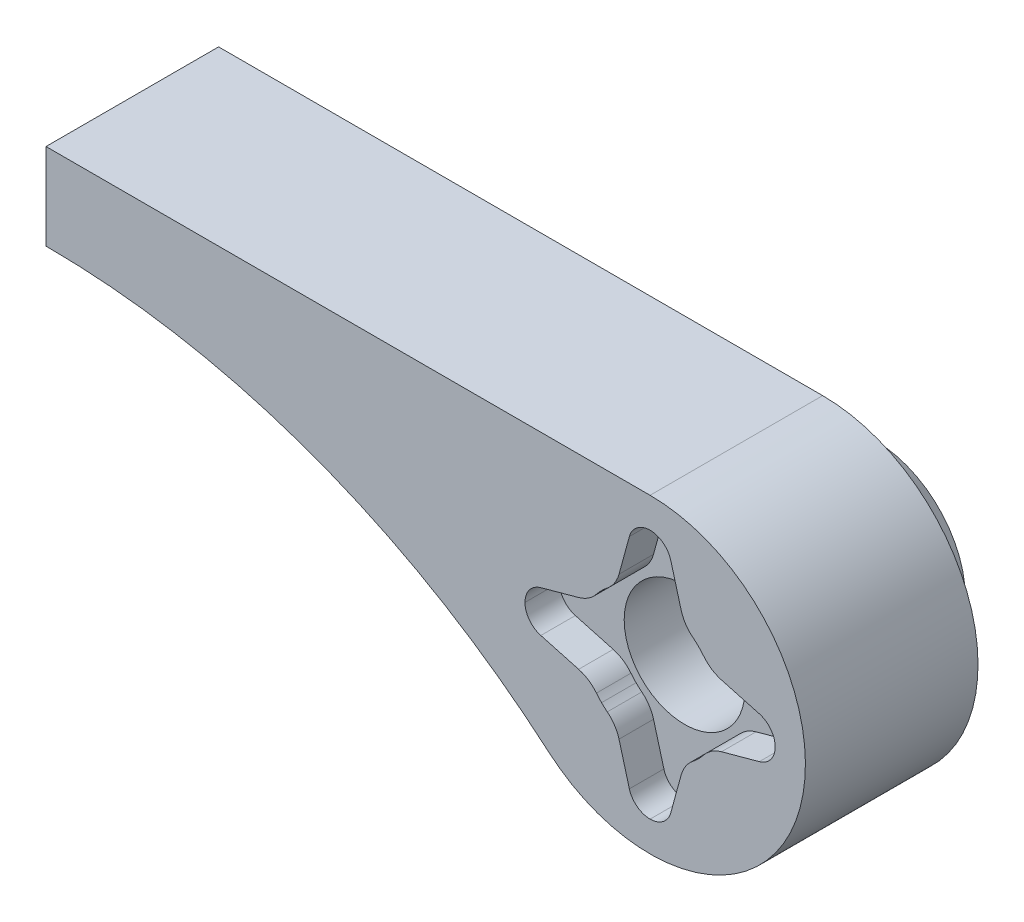
SolidWorks part; units mm, degrees
ref_plane "Front Plane" through (0, 0, 0) normal (0, 0, 1) x (1, 0, 0)
ref_plane "Top Plane" through (0, 0, 0) normal (0, 1, 0) x (1, 0, 0)
ref_plane "Right Plane" through (0, 0, 0) normal (1, 0, 0) x (0, 0, -1)
sketch "Sketch1" plane through (0, 0, 0) normal (0, 0, 1) x (1, 0, 0)
  line L0 (0, -9) -> (-35, -9)
  line L1 (-35, -4) -> (-35, -9)
  circle A0 centre (0, 0) radius 9
  arc A1 (-35, -4) -> (-5.8726, 6.82) centre (-35.0202, 40.6697) ccw
  dimension "D1" = 18
  dimension "D2" = 35
  dimension "D3" = 5
  dimension "D4" = 10.82
extrude "Boss-Extrude1" add sketch "Sketch1" along normal blind 10 contours A0 | A1 L1 L0 A0
move or copy body "Body-Move/Copy1" bodies to move or copy 101 copy no rotation origin (0, 0, 3.5) rotation axis (1, 0, 0) rotation angle 180
sketch "Sketch18" plane through (0, 0, 7) normal (0, 0, 1) x (1, 0, 0)
  line L0 (0, 7.25) -> (0, -7.25) construction
  line L1 (1.2, -6.33) -> (1.8, -4.1378)
  line L2 (0, 0) -> (14.4542, 0) construction
  line L3 (0, 0) -> (10.5914, -10.5914) construction
  line L4 (6.33, -1.2) -> (4.1378, -1.8)
  line L5 (6.33, 1.2) -> (4.1378, 1.8)
  line L6 (1.2, 6.33) -> (1.8, 4.1378)
  line L7 (-1.2, 6.33) -> (-1.8, 4.1378)
  line L8 (-6.33, 1.2) -> (-4.1378, 1.8)
  line L9 (-6.33, -1.2) -> (-4.1378, -1.8)
  line L10 (-1.2, -6.33) -> (-1.8, -4.1378)
  arc A0 (0, -7.25) -> (1.2, -6.33) centre (-0.0057, -6) ccw
  arc A1 (1.8, -4.1378) -> (2.48, -3.1078) centre (3.7276, -4.671) cw
  arc A2 (2.48, -3.1078) -> (2.8116, -2.8116) centre (-0.0153, 0.0185) ccw
  arc A3 (3.1078, -2.48) -> (2.8116, -2.8116) centre (-0.0185, 0.0153) cw
  arc A4 (4.1378, -1.8) -> (3.1078, -2.48) centre (4.671, -3.7276) ccw
  arc A5 (7.25, 0) -> (6.33, -1.2) centre (6, 0.0057) cw
  arc A6 (7.25, 0) -> (6.33, 1.2) centre (6, -0.0057) ccw
  arc A7 (4.1378, 1.8) -> (3.1078, 2.48) centre (4.671, 3.7276) cw
  arc A8 (3.1078, 2.48) -> (2.8116, 2.8116) centre (-0.0185, -0.0153) ccw
  arc A9 (2.48, 3.1078) -> (2.8116, 2.8116) centre (-0.0153, -0.0185) cw
  arc A10 (1.8, 4.1378) -> (2.48, 3.1078) centre (3.7276, 4.671) ccw
  arc A11 (0, 7.25) -> (1.2, 6.33) centre (-0.0057, 6) cw
  arc A12 (0, 7.25) -> (-1.2, 6.33) centre (0.0057, 6) ccw
  arc A13 (-1.8, 4.1378) -> (-2.48, 3.1078) centre (-3.7276, 4.671) cw
  arc A14 (-2.48, 3.1078) -> (-2.8116, 2.8116) centre (0.0153, -0.0185) ccw
  arc A15 (-3.1078, 2.48) -> (-2.8116, 2.8116) centre (0.0185, -0.0153) cw
  arc A16 (-4.1378, 1.8) -> (-3.1078, 2.48) centre (-4.671, 3.7276) ccw
  arc A17 (-7.25, 0) -> (-6.33, 1.2) centre (-6, -0.0057) cw
  arc A18 (-7.25, 0) -> (-6.33, -1.2) centre (-6, 0.0057) ccw
  arc A19 (-4.1378, -1.8) -> (-3.1078, -2.48) centre (-4.671, -3.7276) cw
  arc A20 (-3.1078, -2.48) -> (-2.8116, -2.8116) centre (0.0185, 0.0153) ccw
  arc A21 (-2.48, -3.1078) -> (-2.8116, -2.8116) centre (0.0153, 0.0185) cw
  arc A22 (-1.8, -4.1378) -> (-2.48, -3.1078) centre (-3.7276, -4.671) ccw
  arc A23 (0, -7.25) -> (-1.2, -6.33) centre (0.0057, -6) cw
  point P4 (0, 0)
extrude "Cut-Extrude5" cut sketch "Sketch18" against normal blind 2
sketch "Sketch19" plane through (0, 0, -3) normal (0, 0, -1) x (-1, 0, 0)
  circle A0 centre (0, 0) radius 7
  dimension "D1" = 14
extrude "Boss-Extrude12" add sketch "Sketch19" along normal blind 3 draft 30
sketch "Sketch20" plane through (0, 0, -6) normal (0, 0, -1) x (-1, 0, 0)
  circle A0 centre (0, 0) radius 3.5
  dimension "D1" = 7
extrude "Cut-Extrude6" cut sketch "Sketch20" against normal through all
